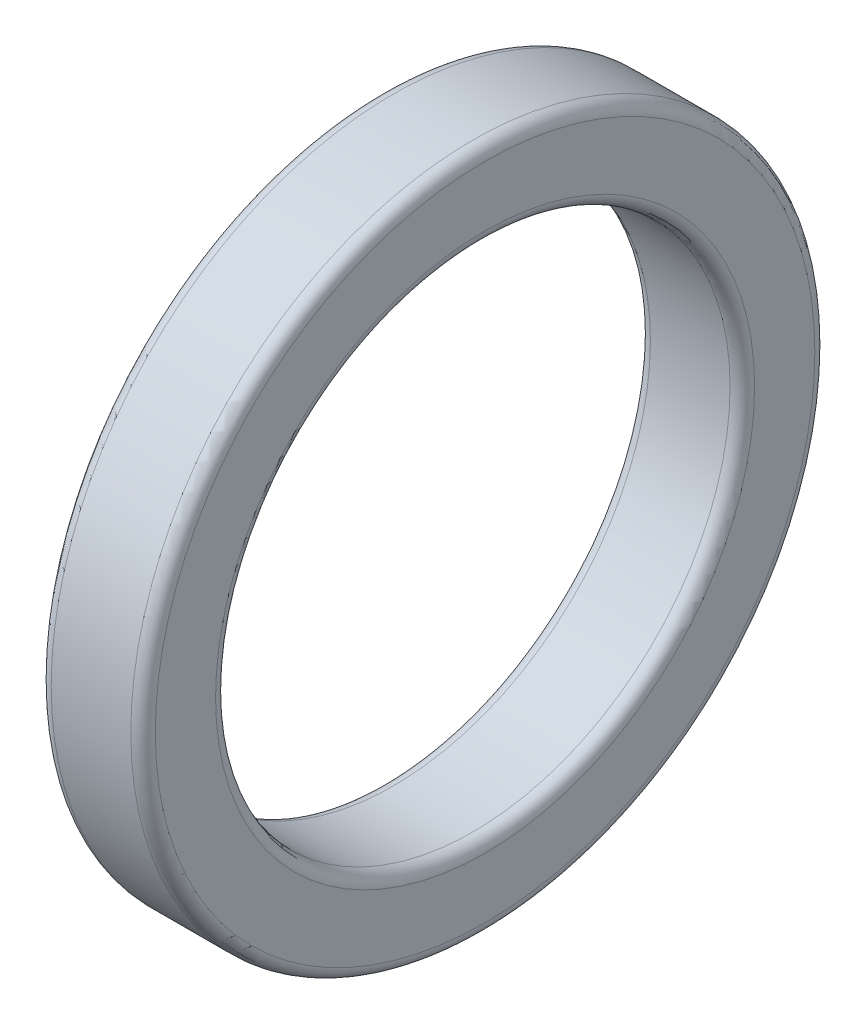
SolidWorks part; units mm, degrees
ref_plane "Front Plane" through (0, 0, 0) normal (0, 0, 1) x (1, 0, 0)
ref_plane "Top Plane" through (0, 0, 0) normal (0, 1, 0) x (1, 0, 0)
ref_plane "Right Plane" through (0, 0, 0) normal (1, 0, 0) x (0, 0, -1)
sketch "Sketch3" plane through (0, 0, 0) normal (1, 0, 0) x (0, 0, -1)
  circle A0 centre (0, 0) radius 279.2
  circle A1 centre (0, 0) radius 210
  dimension "D1" = 558.4
  dimension "D2" = 420
extrude "Boss-Extrude1" add sketch "Sketch3" along normal mid plane 85
fillet "Fillet1" radius 10 4 edges at (-42.5, 0, -210) (-42.5, 0, -279.2) (42.5, 0, -210) (42.5, 0, -279.2)
